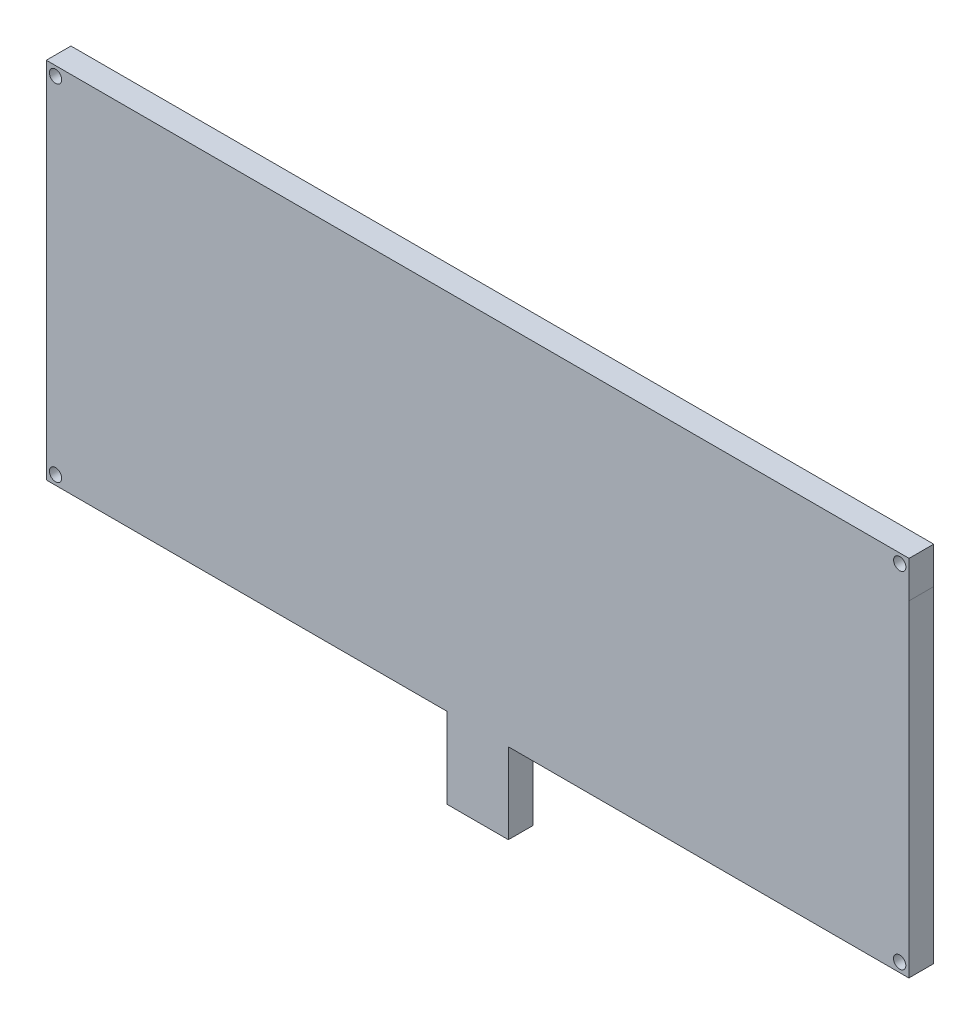
SolidWorks part; units mm, degrees
ref_plane "Front Plane" through (0, 0, 0) normal (0, 0, 1) x (1, 0, 0)
ref_plane "Top Plane" through (0, 0, 0) normal (0, 1, 0) x (1, 0, 0)
ref_plane "Right Plane" through (0, 0, 0) normal (1, 0, 0) x (0, 0, -1)
sketch "Sketch1" plane through (0, 0, 0) normal (0, 0, 1) x (1, 0, 0)
  line L1 (-70, -26.5) -> (70, -26.5)
  line L2 (-70, -26.5) -> (-70, 26.5)
  line L3 (-70, 26.5) -> (70, 26.5)
  line L4 (70, -26.5) -> (70, 26.5)
  line L5 (-70, -26.5) -> (70, 26.5) construction
  line L6 (-70, 26.5) -> (70, -26.5) construction
  point P0 (0, 0)
  point P6 (0, 0)
  dimension "D1" = 53
  dimension "D2" = 140
sketch "Sketch3" plane through (0, 0, 0) normal (0, 0, 1) x (1, 0, 0)
  line L0 (0, -26.5) -> (5, -26.5)
  line L3 (-4.9996, -26.566) -> (-4.9996, -26.5)
  line L4 (-4.9996, -26.566) -> (-4.9996, -39.566)
  line L5 (5, -26.5) -> (5, -39.566)
  line L6 (5, -39.566) -> (-4.9996, -39.566)
  line L7 (-70, -26.5) -> (70, -26.5) construction
  line L8 (-4.9996, -26.5) -> (0, -26.5)
  dimension "D1" = 5
  dimension "D2" = 5
  dimension "D3" = 13
extrude "Boss-Extrude1" add sketch "Sketch3" along normal blind 4
extrude "Boss-Extrude2" add sketch "Sketch1" along normal blind 4
sketch "Sketch4" plane through (0, 0, 0) normal (0, 0, 1) x (1, 0, 0)
  line L0 (-66.9924, -23.5) -> (-70, -26.5)
  line L1 (67.0076, -23.5) -> (70, -26.5)
  line L2 (67.0076, 29.5) -> (70.0301, 32.5)
  circle A0 centre (-68.4962, -25) radius 1
  circle A1 centre (68.5038, -25) radius 1
  circle A2 centre (68.5189, 31) radius 1
sketch "Sketch5" plane through (0, 0, 0) normal (0, 0, 1) x (1, 0, 0)
  line L0 (-70, 26.5) -> (-70, 32.5)
  line L1 (-70, 32.5) -> (70.0301, 32.5)
  line L2 (70.0301, 32.5) -> (70, 26.5)
  line L3 (70, 26.5) -> (-70, 26.5)
  dimension "D1" = 6
extrude "Boss-Extrude3" add sketch "Sketch5" along normal blind 4
sketch "Sketch6" plane through (0, 0, 0) normal (0, 0, 1) x (1, 0, 0)
  line L0 (-70, 32.5) -> (-66.9924, 29.5)
  circle A0 centre (-68.4962, 31) radius 1
extrude "Cut-Extrude1" cut sketch "Sketch6" along normal blind 5 and the other way blind 2 contours L0 A0
extrude "Cut-Extrude4" cut sketch "Sketch4" against normal through all and the other way through all contours A0 | A1 | A2
